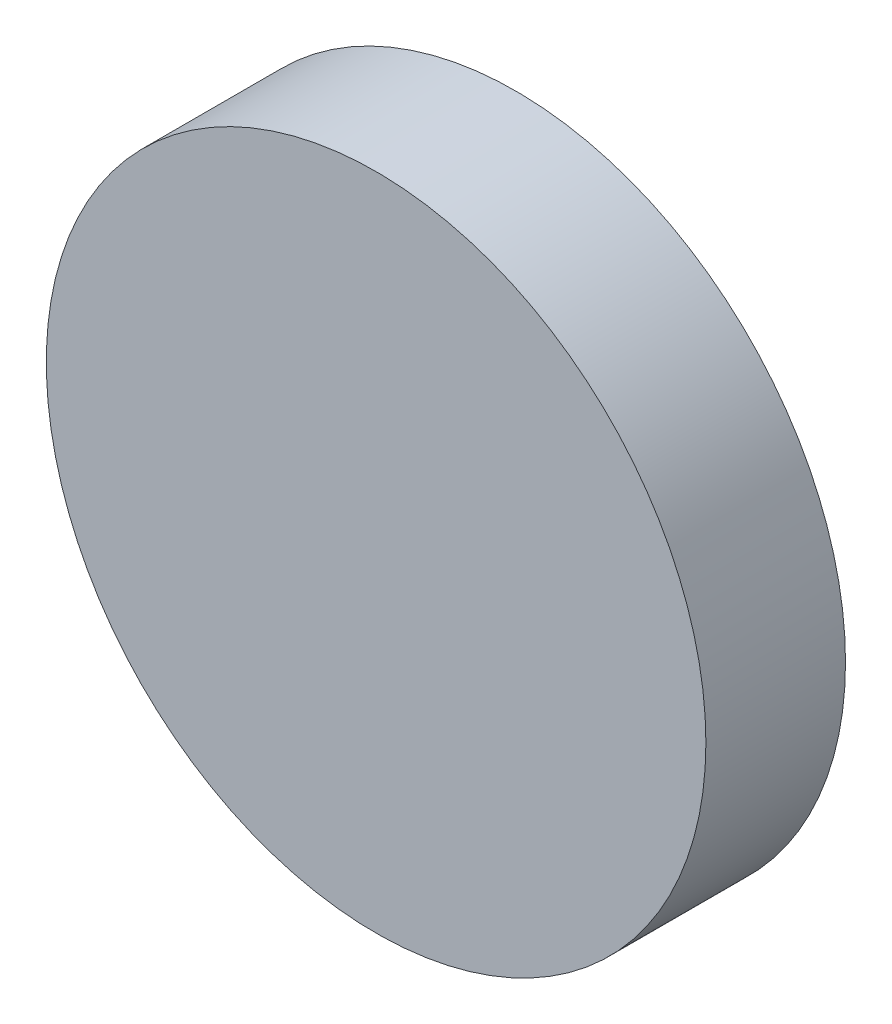
SolidWorks part; units mm, degrees
ref_plane "Front Plane" through (0, 0, 0) normal (0, 0, 1) x (1, 0, 0)
ref_plane "Top Plane" through (0, 0, 0) normal (0, 1, 0) x (1, 0, 0)
ref_plane "Right Plane" through (0, 0, 0) normal (1, 0, 0) x (0, 0, -1)
sketch "Sketch1" plane through (0, 0, 0) normal (0, 0, 1) x (1, 0, 0)
  circle A0 centre (0, 0) radius 7.5
  dimension "D1" = 15
extrude "Boss-Extrude1" add sketch "Sketch1" along normal blind 3.175
